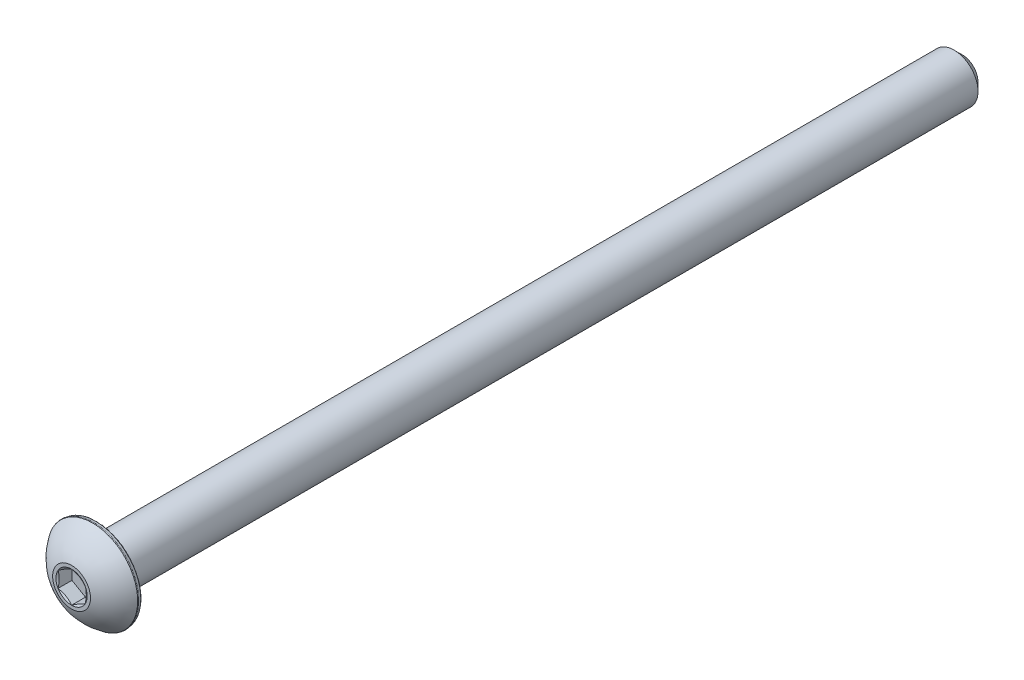
SolidWorks part; units mm, degrees
ref_plane "Front Plane" through (0, 0, 0) normal (0, 0, 1) x (1, 0, 0)
ref_plane "Top Plane" through (0, 0, 0) normal (0, 1, 0) x (1, 0, 0)
ref_plane "Right Plane" through (0, 0, 0) normal (1, 0, 0) x (0, 0, -1)
sketch "Sketch1" plane through (0, 0, 0) normal (1, 0, 0) x (0, 0, -1)
  line L0 (-32.6771, 0) -> (32.6771, 0) construction
  line L1 (-32.6771, 0) -> (-32.6771, 3.3274)
  line L2 (-32.6771, 3.3274) -> (-30.8229, 3.3274)
  line L3 (-30.8229, 3.3274) -> (-30.8229, 1.7526)
  line L4 (-30.8229, 1.7526) -> (32.6771, 1.7526)
  line L5 (32.6771, 1.7526) -> (32.6771, 0)
  line L6 (32.6771, 0) -> (32.6771, -1.7526) construction
  point P2 (0, 0)
  point P4 (31.8833, 0)
  point P9 (31.4865, 1.7526)
  point P10 (31.4865, -1.7526)
  point P12 (-22.5044, 1.7526)
  point P13 (26.0223, 1.7526)
  point P14 (-24.1681, 1.7526)
  point P15 (-31.6573, 0)
  dimension "Head Height" = 1.8542
  dimension "Head Diameter" = 6.6548
  dimension "Length" = 63.5
  dimension "Screw Size Decimal Equivalent" = 3.5052
  dimension "Thread Pitch" = 0.7937
  dimension "D1" = 1.1906
  dimension "D2" = 1.0198
  dimension "D3" = 6.6548
  dimension "D4" = 6.6548
  dimension "D5" = 8.3185
sketch "Sketch2" plane through (0, 0, 0) normal (0, 0, 1) x (1, 0, 0)
  line L0 (0, 1.7526) -> (0, 0) construction
  line L1 (0, 1.1457) -> (-0.9922, 0.5728)
  line L2 (-0.9922, 0.5728) -> (-0.9922, -0.5728)
  line L3 (-0.9922, -0.5728) -> (0, -1.1457)
  line L4 (0, -1.1457) -> (0.9922, -0.5728)
  line L5 (0.9922, -0.5728) -> (0.9922, 0.5728)
  line L6 (0.9922, 0.5728) -> (0, 1.1457)
  circle A0 centre (0, 0) radius 0.9922 construction
  circle A1 centre (0, 0) radius 1.3891
  point P10 (0, 1.3891)
  dimension "D1" = 2.7781
  dimension "Drive Size" = 1.9844
sketch "Sketch3" plane through (0, 0, 0) normal (1, 0, 0) x (0, 0, -1)
  line L0 (-32.6771, 0) -> (-32.6771, 1.3891)
  line L1 (-32.6771, 0) -> (-32.6771, 3.3274) construction
  line L2 (-32.6771, 3.3274) -> (-30.8229, 3.3274) construction
  line L3 (-31.101, 3.3274) -> (-30.8229, 3.2784)
  line L4 (-30.8229, 3.3274) -> (-30.8229, 1.7526) construction
  line L5 (-30.8229, 3.2784) -> (-30.8229, 1.7526)
  line L6 (-32.6771, 0) -> (32.6771, 0) construction
  line L7 (-32.6771, 0) -> (32.6771, 0)
  line L8 (32.6771, 0) -> (32.6771, 1.1573)
  line L9 (32.6771, 1.7526) -> (32.6771, 0) construction
  line L10 (32.6771, 1.1573) -> (32.0818, 1.7526)
  line L11 (-30.8229, 1.7526) -> (32.6771, 1.7526) construction
  line L12 (32.0818, 1.7526) -> (-30.8229, 1.7526)
  arc A0 (-32.6771, 1.3891) -> (-31.101, 3.3274) centre (-28.9888, 0) cw
  dimension "D1" = 0.2781
  dimension "D2" = 10
  dimension "D3" = 45
  dimension "D4" = 0.5953
revolve "Revolve1" add sketch "Sketch3" angle 360 about L7
sketch "Sketch4" plane through (0, 0, 32.6771) normal (0, 0, 1) x (1, 0, 0)
  line L0 (-0.9922, -0.5728) -> (0, -1.1457) construction
  line L1 (-0.9922, 0.5728) -> (-0.9922, -0.5728) construction
  line L2 (0, 1.1457) -> (-0.9922, 0.5728) construction
  line L3 (0.9922, 0.5728) -> (0, 1.1457) construction
  line L4 (0.9922, -0.5728) -> (0.9922, 0.5728) construction
  line L5 (0, -1.1457) -> (0.9922, -0.5728) construction
  line L6 (-0.9922, -0.5728) -> (0, -1.1457)
  line L7 (-0.9922, 0.5728) -> (-0.9922, -0.5728)
  line L8 (0, 1.1457) -> (-0.9922, 0.5728)
  line L9 (0.9922, 0.5728) -> (0, 1.1457)
  line L10 (0.9922, -0.5728) -> (0.9922, 0.5728)
  line L11 (0, -1.1457) -> (0.9922, -0.5728)
extrude "Cut-Extrude1" cut sketch "Sketch4" against normal up to vertex (1.0198 mm away) up to point (0, 0, 31.6573)
sketch "Sketch5" plane through (0, 0, 32.6771) normal (0, 0, 1) x (1, 0, 0)
  circle A0 centre (0, 0) radius 1.1457
extrude "Cut-Extrude2" cut sketch "Sketch5" against normal up to vertex (1.0198 mm away) draft 60 up to point (0, 0, 31.6573)
fillet "Fillet1" radius 0.0927 2 edges at (3.3274, 0, 31.101) (3.2784, 0, 30.8229)
equation "\"D1@Sketch1\"=\"Thread Pitch@Sketch1\"*1.5"
equation "\"D2@Sketch1\"=0.55*\"Head Height@Sketch1\""
equation "\"D1@Sketch2\"=\"Drive Size@Sketch2\"*1.4"
equation "\"D1@Sketch3\"=0.15*\"Head Height@Sketch1\""
equation "\"D4@Sketch3\"=0.75*\"Thread Pitch@Sketch1\""
equation "\"D1@Fillet1\"=.05*\"Head Height@Sketch1\""
equation "\"D3@Sketch1\"=\"Head Diameter@Sketch1\""
equation "\"D4@Sketch1\"=\"Head Diameter@Sketch1\""
equation "\"D5@Sketch1\"=\"D3@Sketch1\"*1.25"
